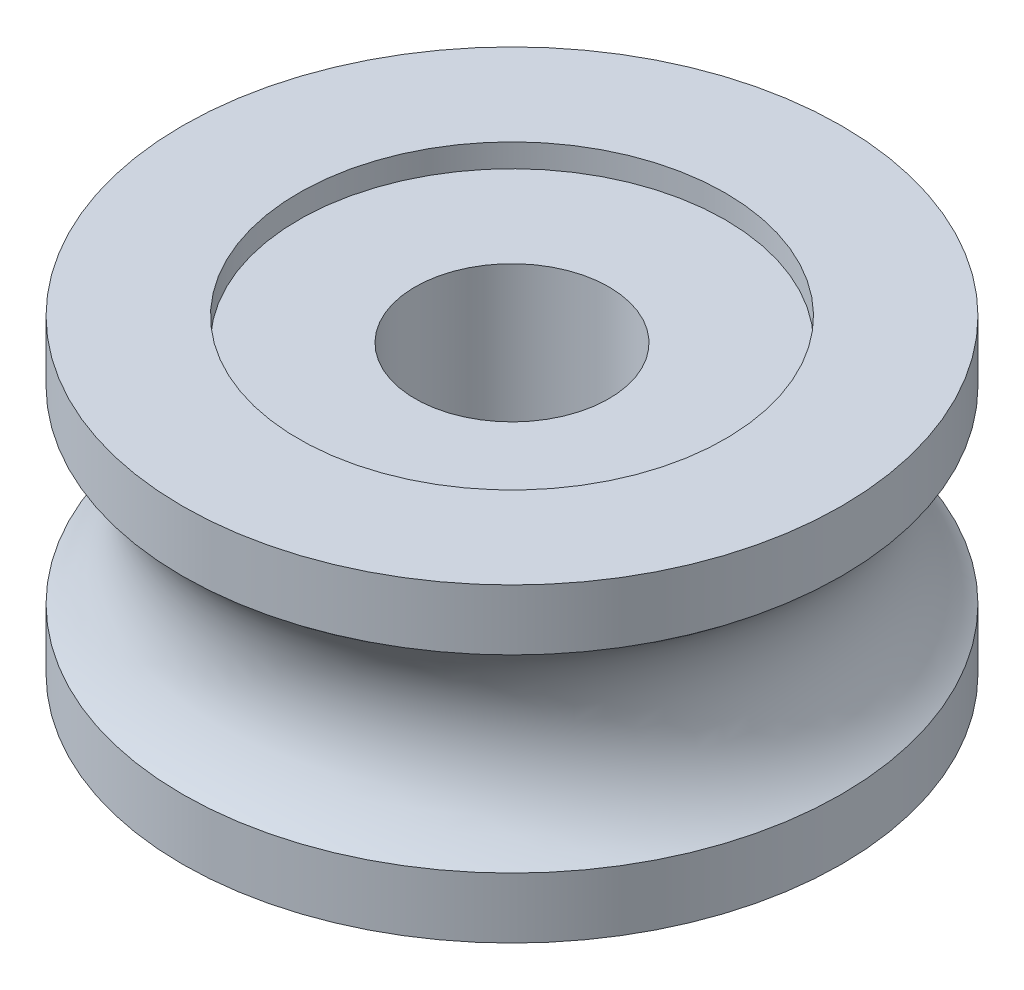
SolidWorks part; units mm, degrees
ref_plane "Спереди" through (0, 0, 0) normal (0, 0, 1) x (1, 0, 0)
ref_plane "Сверху" through (0, 0, 0) normal (0, 1, 0) x (1, 0, 0)
ref_plane "Справа" through (0, 0, 0) normal (1, 0, 0) x (0, 0, -1)
sketch "Эскиз1" plane through (0, 0, 0) normal (0, 0, 1) x (1, 0, 0)
  line L0 (2.5, -4.6) -> (2.5, 4.6)
  line L3 (8.5, -2.8) -> (4.3, -2.8)
  line L4 (4.3, -2.8) -> (4.3, -4.6)
  line L5 (4.3, -4.6) -> (2.5, -4.6)
  line L6 (0, 0) -> (0, 5.6) construction
  line L7 (8.5, -2.8) -> (8.5, -1.2367)
  line L8 (8.5, 5.2) -> (8.5, 3.6367)
  line L9 (8.5, 5.2) -> (5.5, 5.2)
  line L10 (5.5, 5.2) -> (5.5, 4.6)
  line L11 (5.5, 4.6) -> (2.5, 4.6)
  arc A0 (8.5, 3.6367) -> (8.5, -1.2367) centre (10.25, 1.2) ccw
  point P2 (2.5, 0)
  dimension "D2" = 3
  dimension "D1" = 2.5
  dimension "D3" = 4.3
  dimension "D4" = 8
  dimension "D5" = 10.25
  dimension "D6" = 9.8
  dimension "D7" = 8.5
  dimension "D8" = 0.6
  dimension "D9" = 5.5
revolve "Повернуть1" add sketch "Эскиз1" angle 360 about L6
ref_plane "Плоскость1" through (0, 1.2, 0) normal (0, 1, 0) x (1, 0, 0)
